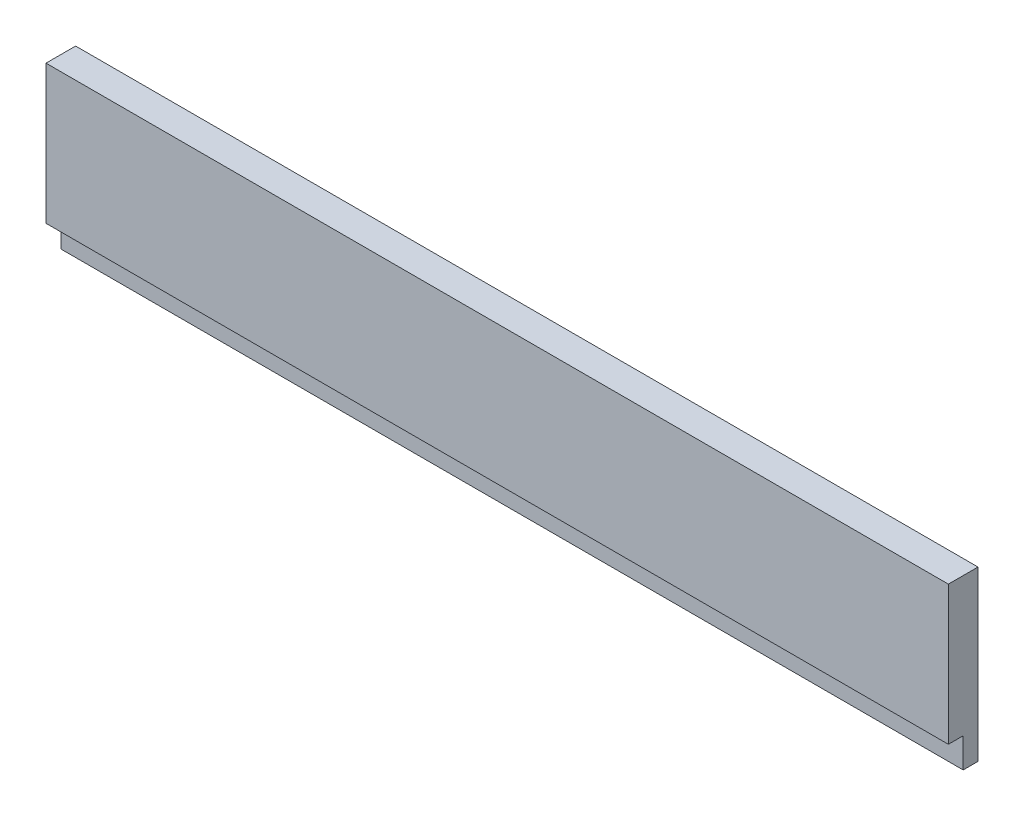
SolidWorks part; units mm, degrees
material "Pino"
ref_plane "Alzado" through (0, 0, 0) normal (0, 0, 1) x (1, 0, 0)
ref_plane "Planta" through (0, 0, 0) normal (0, 1, 0) x (1, 0, 0)
ref_plane "Vista lateral" through (0, 0, 0) normal (1, 0, 0) x (0, 0, -1)
sketch "Croquis1" plane through (0, 0, 0) normal (0, 0, 1) x (1, 0, 0)
  line L0 (-134.3294, -40.1786) -> (-134.3294, 84.8214)
  line L1 (-134.3294, 84.8214) -> (535.6706, 84.8214)
  line L2 (535.6706, 84.8214) -> (535.6706, -40.1786)
  line L3 (535.6706, -40.1786) -> (-134.3294, -40.1786)
  dimension "D1" = 125
  dimension "D2" = 670
extrude "Saliente-Extruir1" add sketch "Croquis1" along normal blind 22
sketch "Croquis2" plane through (-134.3294, 0, 0) normal (-1, 0, 0) x (0, 0, 1)
  line L0 (11, -40.1786) -> (11, -18.1786)
  line L1 (22, -40.1786) -> (0, -40.1786) construction
  line L2 (11, -18.1786) -> (22, -18.1786)
  line L3 (22, 84.8214) -> (22, -40.1786) construction
  line L4 (11, -40.1786) -> (22, -40.1786)
  line L5 (22, -40.1786) -> (22, -18.1786)
  dimension "D1" = 22
extrude "Cortar-Extruir1" cut sketch "Croquis2" against normal through all
